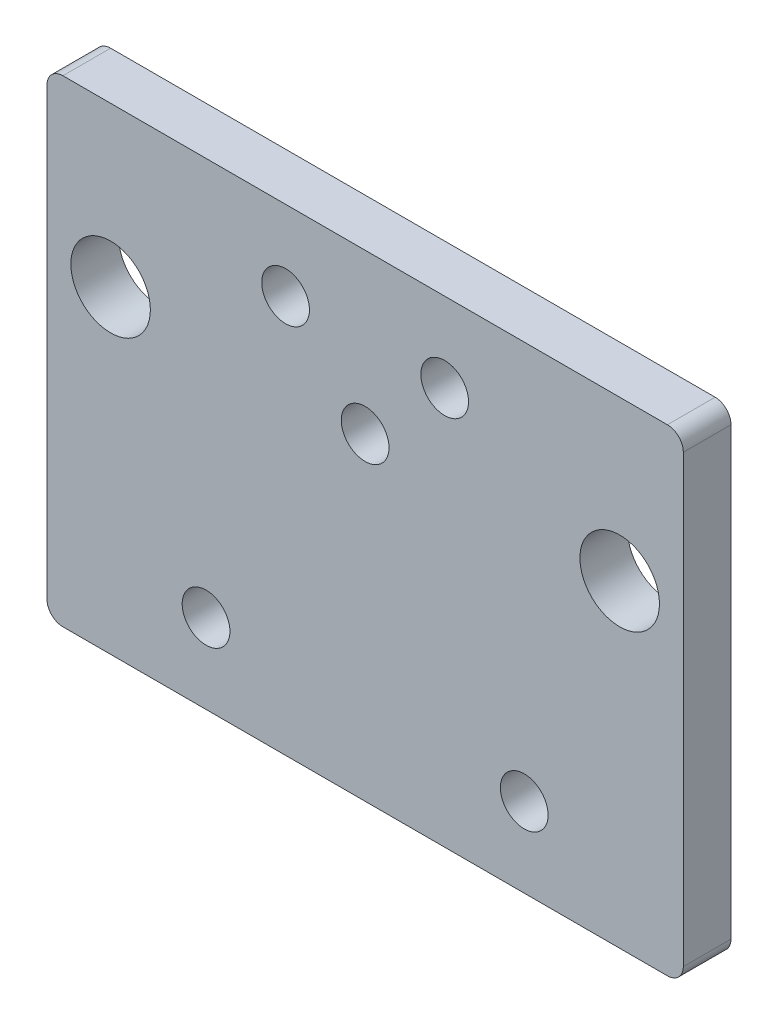
SolidWorks part; units mm, degrees
ref_plane "前视基准面" through (0, 0, 0) normal (0, 0, 1) x (1, 0, 0)
ref_plane "上视基准面" through (0, 0, 0) normal (0, 1, 0) x (1, 0, 0)
ref_plane "右视基准面" through (0, 0, 0) normal (1, 0, 0) x (0, 0, -1)
sketch "草图1" plane through (0, 0, 0) normal (0, 0, 1) x (1, 0, 0)
  line L1 (20, -10) -> (-20, -10)
  line L2 (20, -10) -> (20, 10)
  line L3 (20, 10) -> (-20, 10)
  line L4 (-20, -10) -> (-20, 10)
  line L5 (20, -10) -> (-20, 10) construction
  line L6 (20, 10) -> (-20, -10) construction
  circle A0 centre (-16, 0) radius 2.5
  circle A1 centre (16, 0) radius 2.5
  point P0 (0, 0)
  dimension "D5" = 5
  dimension "D6" = 5
  dimension "D1" = 40
  dimension "D2" = 20
  dimension "D3" = 16
  dimension "D4" = 16
extrude "凸台-拉伸1" add sketch "草图1" along normal blind 3
sketch "草图2" plane through (0, 0, 3) normal (0, 0, 1) x (1, 0, 0)
  circle A0 centre (0, 0) radius 1.5
  dimension "D1" = 3
extrude "切除-拉伸1" cut sketch "草图2" against normal blind 3
sketch "草图4" plane through (0, 0, 3) normal (0, 0, 1) x (1, 0, 0)
  line L1 (-20, -10) -> (20, -10)
  line L2 (-20, -10) -> (-20, -20)
  line L3 (-20, -20) -> (20, -20)
  line L4 (20, -10) -> (20, -20)
  line L5 (-20, -10) -> (20, -20) construction
  line L6 (-20, -20) -> (20, -10) construction
  point P4 (0, -15)
  dimension "D1" = 10
extrude "凸台-拉伸2" add sketch "草图4" against normal blind 3
sketch "草图5" plane through (0, 0, 3) normal (0, 0, 1) x (1, 0, 0)
  line L0 (-20, -20) -> (20, -20) construction
  circle A0 centre (-10, -15) radius 1.5
  circle A1 centre (10, -15) radius 1.5
  point P7 (0, 0)
  dimension "D2" = 3
  dimension "D3" = 3
  dimension "D1" = 20
  dimension "D4" = 10
  dimension "D5" = 5
extrude "切除-拉伸2" cut sketch "草图5" against normal blind 10
sketch "草图6" plane through (0, 0, 3) normal (0, 0, 1) x (1, 0, 0)
  line L0 (20, 10) -> (-20, 10) construction
  circle A0 centre (-5, 5) radius 1.5
  circle A1 centre (5, 5) radius 1.5
  point P7 (0, 0)
  point P8 (0, 0)
  dimension "D1" = 3
  dimension "D2" = 3
  dimension "D3" = 10
  dimension "D4" = 5
  dimension "D5" = 5
extrude "切除-拉伸3" cut sketch "草图6" against normal blind 10
fillet "圆角1" radius 1 4 edges at (-20, -20, 1.5) (20, -20, 1.5) (20, 10, 1.5) (-20, 10, 1.5)
